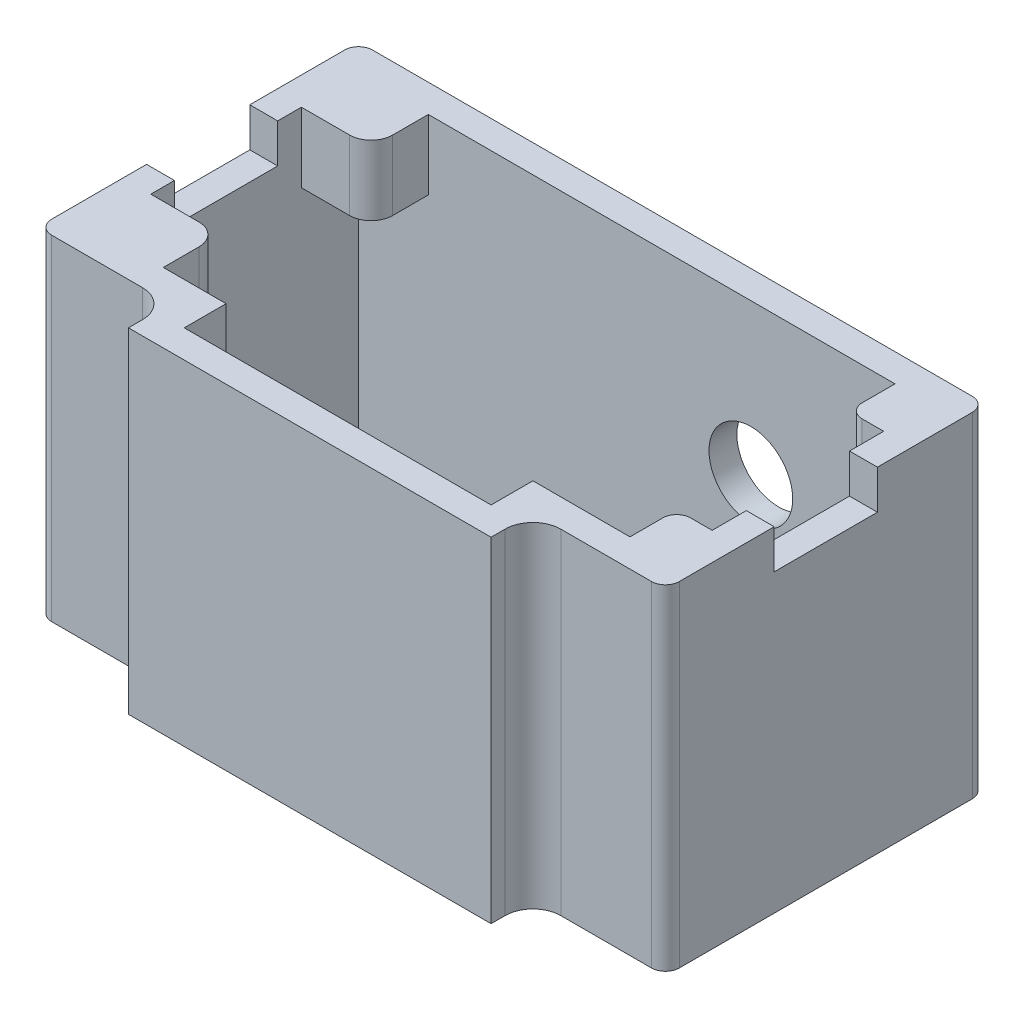
SolidWorks part; units mm, degrees
ref_plane "Front Plane" through (0, 0, 0) normal (0, 0, 1) x (1, 0, 0)
ref_plane "Top Plane" through (0, 0, 0) normal (0, 1, 0) x (1, 0, 0)
ref_plane "Right Plane" through (0, 0, 0) normal (1, 0, 0) x (0, 0, -1)
sketch "Sketch1" plane through (0, 0, 0) normal (0, 1, 0) x (1, 0, 0)
  line L1 (-28.575, -14.605) -> (28.575, -14.605)
  line L2 (-28.575, -14.605) -> (-28.575, 14.605)
  line L3 (-28.575, 14.605) -> (28.575, 14.605)
  line L4 (28.575, -14.605) -> (28.575, 14.605)
  line L5 (-28.575, -14.605) -> (28.575, 14.605) construction
  line L6 (-28.575, 14.605) -> (28.575, -14.605) construction
  point P0 (0, 0)
  dimension "D1" = 57.15
  dimension "D2" = 29.21
extrude "Boss-Extrude1" add sketch "Sketch1" along normal blind 30.48
shell "Shell1" thickness 2.54
sketch "Sketch2" plane through (0, 0, 0) normal (0, -1, 0) x (1, 0, 0)
  line L0 (0, 0) -> (37.592, 0) construction
  line L1 (28.575, 14.605) -> (28.575, -14.605) construction
  line L2 (24.13, -6.477) -> (13.462, -6.477)
  line L3 (24.13, -6.477) -> (24.13, 6.477)
  line L4 (24.13, 6.477) -> (13.462, 6.477)
  line L5 (13.462, -6.477) -> (13.462, 6.477)
  line L6 (24.13, -6.477) -> (13.462, 6.477) construction
  line L7 (24.13, 6.477) -> (13.462, -6.477) construction
  point P3 (18.796, 0)
  dimension "D1" = 12.954
  dimension "D2" = 10.668
  dimension "D3" = 4.445
extrude "Cut-Extrude1" cut sketch "Sketch2" against normal up to surface (2.54 mm away) up to face at (0, 2.54, 0)
sketch "Sketch3" plane through (0, 30.48, 0) normal (0, 1, 0) x (1, 0, 0)
  line L0 (0, 0) -> (-37.2945, 0) construction
  line L1 (-26.035, 12.065) -> (-26.035, -12.065) construction
  line L17 (-26.035, 12.065) -> (-26.035, 6.858)
  line L19 (-19.685, 12.065) -> (-19.685, 8.8138)
  line L20 (-21.6408, 6.858) -> (-26.035, 6.858)
  line L21 (-19.685, -12.065) -> (-19.685, -8.8138)
  line L22 (-21.6408, -6.858) -> (-26.035, -6.858)
  line L23 (-26.035, -12.065) -> (-26.035, -6.858)
  line L24 (-19.685, -12.065) -> (-26.035, -12.065)
  line L25 (26.035, 12.065) -> (-26.035, 12.065) construction
  line L26 (26.035, 12.065) -> (22.8092, 12.065)
  line L27 (22.8092, 12.065) -> (22.8092, 9.0805)
  line L28 (26.035, 7.8105) -> (26.035, 12.065)
  line L29 (26.035, -12.065) -> (26.035, 12.065) construction
  line L30 (-26.035, 12.065) -> (-19.685, 12.065)
  line L34 (26.035, -12.065) -> (26.035, 12.065) construction
  line L35 (26.035, 7.8105) -> (24.0792, 7.8105)
  line L36 (26.035, -7.8105) -> (26.035, -12.065)
  line L37 (26.035, -12.065) -> (22.8092, -12.065)
  line L38 (22.8092, -12.065) -> (22.8092, -9.0805)
  line L39 (26.035, -7.8105) -> (24.0792, -7.8105)
  arc A6 (-19.685, 8.8138) -> (-21.6408, 6.858) centre (-21.6408, 8.8138) cw
  arc A7 (-19.685, -8.8138) -> (-21.6408, -6.858) centre (-21.6408, -8.8138) ccw
  arc A10 (22.8092, 9.0805) -> (24.0792, 7.8105) centre (24.0792, 9.0805) ccw
  arc A11 (22.8092, -9.0805) -> (24.0792, -7.8105) centre (24.0792, -9.0805) cw
  dimension "D2" = 13.716
  dimension "D3" = 1.9558
  dimension "D5" = 1.27
  dimension "D1" = 6.35
  dimension "D4" = 15.621
  dimension "D6" = 45.72
extrude "Boss-Extrude2" add sketch "Sketch3" against normal blind 6.35
sketch "Sketch4" plane through (-28.575, 0, 0) normal (-1, 0, 0) x (0, 0, 1)
  line L0 (-14.605, 30.48) -> (14.605, 30.48) construction
  line L1 (-14.605, 30.48) -> (14.605, 30.48) construction
  line L3 (-4.699, 26.924) -> (4.699, 26.924)
  line L4 (-4.699, 26.924) -> (-4.699, 34.036)
  line L5 (-4.699, 34.036) -> (4.699, 34.036)
  line L6 (4.699, 26.924) -> (4.699, 34.036)
  line L7 (-4.699, 26.924) -> (4.699, 34.036) construction
  line L8 (-4.699, 34.036) -> (4.699, 26.924) construction
  point P2 (0, 30.48)
  dimension "D1" = 9.398
  dimension "D2" = 3.556
extrude "Cut-Extrude2" cut sketch "Sketch4" against normal up to surface (57.15 mm away) contours L4 L3 L6 L5 up to face at (28.575, 15.24, 0)
sketch "Sketch6" plane through (0, 30.48, 0) normal (0, 1, 0) x (1, 0, 0)
  line L0 (-28.575, -14.605) -> (28.575, -14.605) construction
  line L5 (-16.51, -14.605) -> (16.51, -14.605)
  line L6 (-16.51, -14.605) -> (-16.51, -18.415)
  line L7 (-16.51, -18.415) -> (16.51, -18.415)
  line L8 (16.51, -18.415) -> (16.51, -14.605)
  line L9 (0, 0) -> (0, -27.7045) construction
  point P9 (0, -14.605)
  dimension "D1" = 3.81
  dimension "D2" = 33.02
extrude "Boss-Extrude3" add sketch "Sketch6" against normal up to surface (30.48 mm away) up to face at (18.796, 0, 0)
sketch "Sketch7" plane through (0, 30.48, 0) normal (0, 1, 0) x (1, 0, 0)
  line L0 (-16.51, -18.415) -> (16.51, -18.415) construction
  line L1 (-19.685, -12.065) -> (22.8092, -12.065) construction
  line L2 (-16.51, -18.415) -> (16.51, -18.415)
  line L3 (-13.97, -12.065) -> (13.97, -12.065)
  line L4 (-13.97, -12.065) -> (-13.97, -15.875)
  line L5 (-13.97, -15.875) -> (13.97, -15.875)
  line L6 (13.97, -15.875) -> (13.97, -12.065)
  line L7 (-16.51, -14.605) -> (-16.51, -18.415) construction
  line L8 (16.51, -18.415) -> (16.51, -14.605) construction
  line M29 (22.8092, -12.065) -> (-19.685, -12.065)
  dimension "D1" = 2.54
  dimension "D2" = 2.54
  dimension "D3" = 2.54
extrude "Cut-Extrude3" cut sketch "Sketch7" against normal offset from surface (27.94 mm away) 2.54 contours L5 L6 L4 M29 up to face at (18.796, 0, 0)
fillet "Fillet1" radius 2.54 2 edges at (16.51, 15.24, 14.605) (-16.51, 15.24, 14.605)
fillet "Fillet2" radius 1.27 4 edges at (28.575, 15.24, 14.605) (28.575, 15.24, -14.605) (-28.575, 15.24, -14.605) (-28.575, 15.24, 14.605)
sketch "Sketch8" plane through (0, 0, -14.605) normal (0, 0, -1) x (-1, 0, 0)
  circle A0 centre (-9.6841, 16.7451) radius 3.81
  point P2 (-18.1654, 9.4782)
  point P3 (-18.5713, 12.4007)
  point P4 (-18.578, 17.0188)
  point P5 (-9.6841, 16.7451)
  dimension "D1" = 7.62
extrude "Cut-Extrude4" cut sketch "Sketch8" against normal up to surface (2.54 mm away) up to face at (0.781, 20.32, -12.065)
